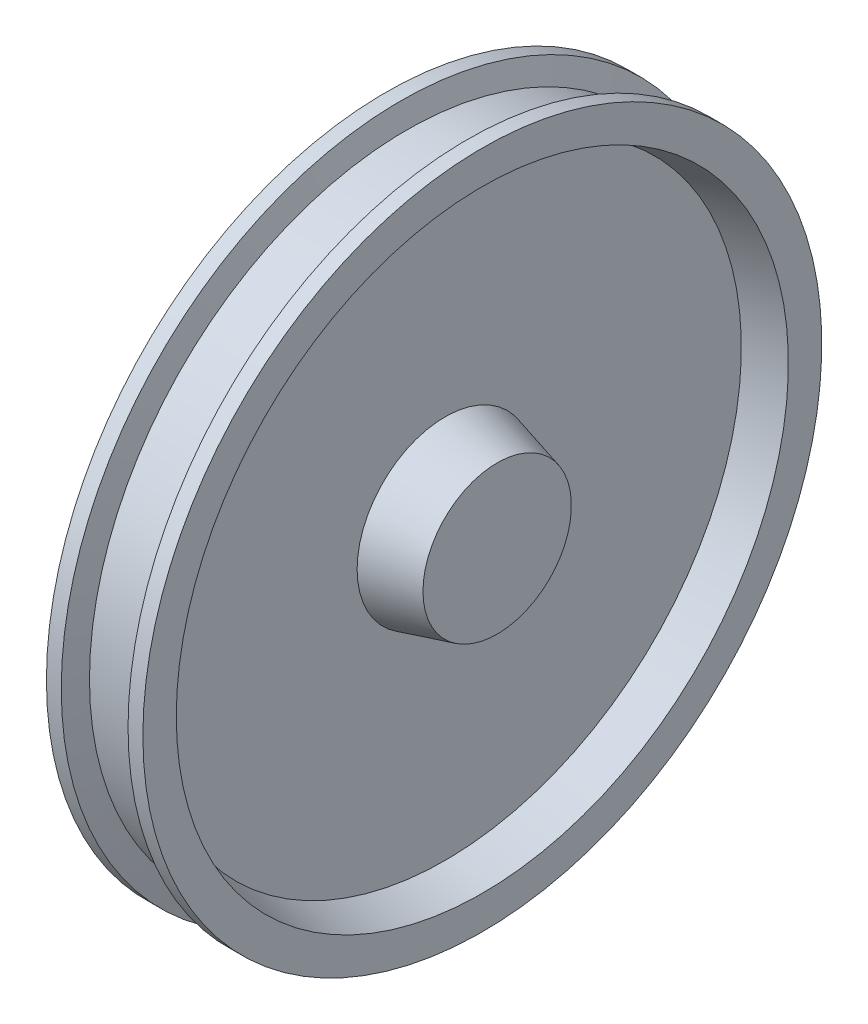
SolidWorks part; units mm, degrees
material "1060 Alloy"
ref_plane "Front Plane" through (0, 0, 0) normal (0, 0, 1) x (1, 0, 0)
ref_plane "Top Plane" through (0, 0, 0) normal (0, 1, 0) x (1, 0, 0)
ref_plane "Right Plane" through (0, 0, 0) normal (1, 0, 0) x (0, 0, -1)
sketch "Sketch1" plane through (0, 0, 0) normal (0, 1, 0) x (1, 0, 0)
  line L0 (0, 427.5) -> (0, -257.8979) construction
  line L1 (-372, 0) -> (372, 0) construction
  line L2 (-85, 0) -> (85, 0) construction
  line L3 (85, 0) -> (85, 100)
  line L4 (85, 100) -> (15, 118.7564)
  line L5 (15, 118.7564) -> (15, 399.1025)
  line L6 (15, 399.1025) -> (65, 412.5)
  line L7 (65, 412.5) -> (65, 457.5)
  line L8 (65, 457.5) -> (45, 457.5)
  line L9 (45, 457.5) -> (36.9615, 427.5)
  line L10 (36.9615, 427.5) -> (-36.9615, 427.5)
  line L11 (15, 118.7564) -> (91.7849, 118.7564) construction
  line L12 (-85, 0) -> (-85, 100)
  line L13 (36.9615, 427.5) -> (36.9615, 457.5) construction
  line L14 (15, 399.1025) -> (32.4139, 399.1025) construction
  line L15 (-85, 100) -> (-15, 118.7564)
  line L16 (-15, 118.7564) -> (-15, 399.1025)
  line L17 (-15, 399.1025) -> (-65, 412.5)
  line L18 (-65, 412.5) -> (-65, 457.5)
  line L19 (-65, 457.5) -> (-45, 457.5)
  line L20 (-45, 457.5) -> (-36.9615, 427.5)
  line L21 (-85, 0) -> (85, 0)
  point P2 (0, 0)
  point P4 (0, 0)
  point P8 (0, 0)
  point P21 (0, 0)
  dimension "D2" = 15
  dimension "D3" = 100
  dimension "D4" = 45
  dimension "D5" = 20
  dimension "D6" = 30
  dimension "D7" = 15
  dimension "D8" = 15
  dimension "D9" = 65
  dimension "D10" = 85
  dimension "D11" = 457.5
  dimension "D12" = 30
revolve "Revolve1" add sketch "Sketch1" angle 360 about L21
equation "\"A\"= 130mm"
equation "\"B\"= 915mm"
